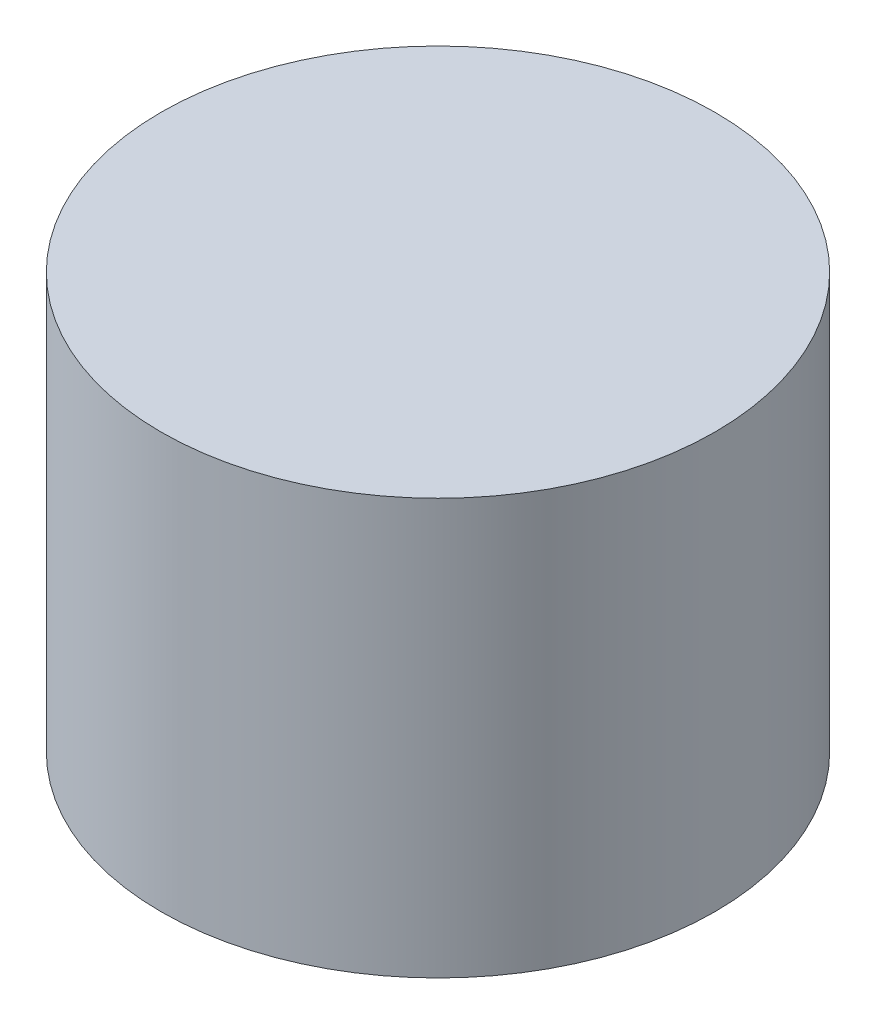
SolidWorks part; units mm, degrees
ref_plane "Front Plane" through (0, 0, 0) normal (0, 0, 1) x (1, 0, 0)
ref_plane "Top Plane" through (0, 0, 0) normal (0, 1, 0) x (1, 0, 0)
ref_plane "Right Plane" through (0, 0, 0) normal (1, 0, 0) x (0, 0, -1)
sketch "Sketch1" plane through (0, 0, 0) normal (0, 1, 0) x (1, 0, 0)
  circle A0 centre (0, 0) radius 50.8
  dimension "D1" = 101.6
extrude "Boss-Extrude1" add sketch "Sketch1" along normal blind 76.2
